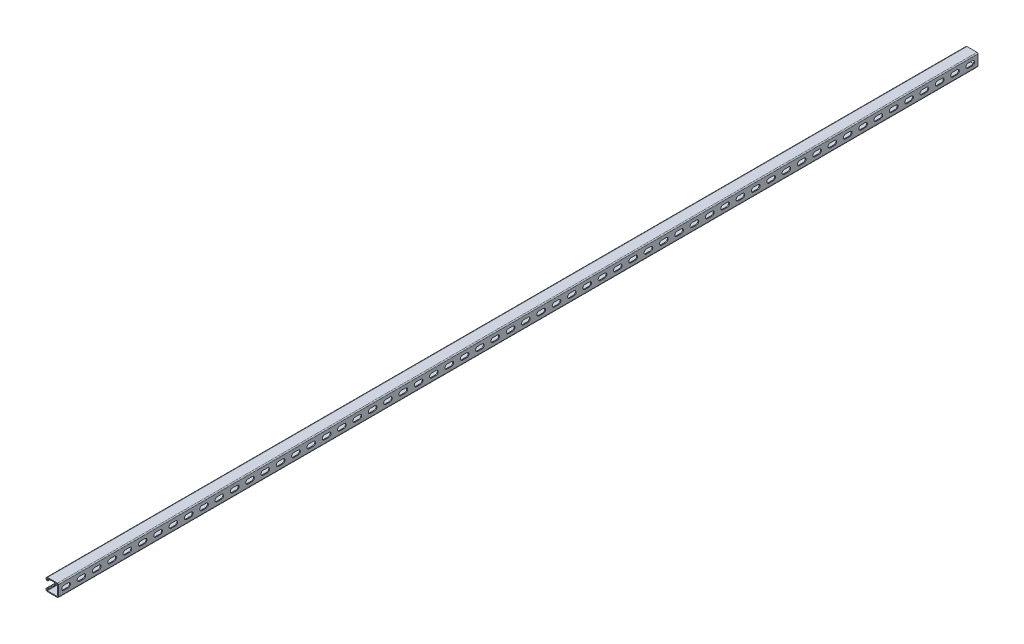
SolidWorks part; units mm, degrees
ref_plane "Front Plane" through (0, 0, 0) normal (0, 0, 1) x (1, 0, 0)
ref_plane "Top Plane" through (0, 0, 0) normal (0, 1, 0) x (1, 0, 0)
ref_plane "Right Plane" through (0, 0, 0) normal (1, 0, 0) x (0, 0, -1)
sketch "Sketch1" plane through (0, 0, 0) normal (0, 0, 1) x (1, 0, 0)
  line L0 (0, 0) -> (-41.275, 0) construction
  line L3 (-41.275, 20.6375) -> (0, 20.6375) construction
  line L4 (-41.275, 20.6375) -> (-41.275, -20.6375) construction
  line L5 (-41.275, -20.6375) -> (0, -20.6375) construction
  line L6 (0, 20.6375) -> (0, -20.6375) construction
  line L7 (-36.2267, 20.6375) -> (-3.4607, 20.6375)
  line L8 (0, 17.1767) -> (0, -17.1767)
  line L9 (-2.794, -17.1767) -> (-2.794, 17.1767)
  line L10 (-3.4608, 17.8435) -> (-36.2267, 17.8435)
  line L11 (-41.275, 15.5892) -> (-41.275, 14.5732)
  line L12 (-37.8142, 11.1125) -> (-35.5346, 11.1125)
  line L14 (-35.5346, 13.9065) -> (-37.8142, 13.9065)
  line L15 (-38.481, 14.5732) -> (-38.481, 15.5892)
  line L16 (-38.481, -14.5733) -> (-38.481, -15.5893)
  line L17 (-35.5346, -13.9065) -> (-37.8142, -13.9065)
  line L18 (-37.8142, -11.1125) -> (-35.5346, -11.1125)
  line L19 (-41.275, -15.5893) -> (-41.275, -14.5733)
  line L20 (-3.4607, -17.8435) -> (-36.2267, -17.8435)
  line L21 (-36.2267, -20.6375) -> (-3.4607, -20.6375)
  line L22 (-2.794, -20.6375) -> (-2.794, 20.6375) construction
  arc A1 (0, 17.1767) -> (-3.4607, 20.6375) centre (-3.4607, 17.1767) ccw
  arc A2 (-2.794, 17.1767) -> (-3.4608, 17.8435) centre (-3.4607, 17.1767) ccw
  arc A4 (-36.2267, 20.6375) -> (-41.275, 15.5892) centre (-36.2267, 15.5892) ccw
  arc A5 (-41.275, 14.5732) -> (-37.8142, 11.1125) centre (-37.8142, 14.5732) ccw
  arc A6 (-35.5346, 11.1125) -> (-35.5346, 13.9065) centre (-35.5346, 12.5095) ccw
  arc A7 (-37.8142, 13.9065) -> (-38.481, 14.5732) centre (-37.8142, 14.5732) cw
  arc A8 (-38.481, 15.5892) -> (-36.2267, 17.8435) centre (-36.2267, 15.5892) cw
  arc A9 (-38.481, -15.5893) -> (-36.2267, -17.8435) centre (-36.2267, -15.5893) ccw
  arc A10 (-37.8142, -13.9065) -> (-38.481, -14.5733) centre (-37.8142, -14.5733) ccw
  arc A11 (-35.5346, -11.1125) -> (-35.5346, -13.9065) centre (-35.5346, -12.5095) cw
  arc A12 (-41.275, -14.5733) -> (-37.8142, -11.1125) centre (-37.8142, -14.5733) cw
  arc A13 (-36.2267, -20.6375) -> (-41.275, -15.5893) centre (-36.2267, -15.5893) cw
  arc A14 (-2.794, -17.1767) -> (-3.4607, -17.8435) centre (-3.4607, -17.1767) cw
  arc A15 (0, -17.1767) -> (-3.4607, -20.6375) centre (-3.4607, -17.1767) cw
  point P24 (0, 20.6375)
  point P65 (-2.794, 0)
  dimension "D1" = 3.4608
  dimension "D2" = 5.0482
  dimension "D3" = 3.4608
  dimension "Ht." = 41.275
  dimension "Wd." = 41.275
  dimension "Thk." = 2.794
  dimension "D4" = 9.525
  dimension "D5" = 7.1374
extrude "Boss-Extrude1" add sketch "Sketch1" against normal blind 2540
sketch "Sketch4" plane through (0, 0, -2540) normal (0, 0, -1) x (-1, 0, 0)
  line L14 (36.2267, 20.6375) -> (3.4607, 20.6375)
  line L15 (0, 17.1767) -> (0, -17.1767)
  line L16 (3.4607, -20.6375) -> (36.2267, -20.6375)
  line L17 (41.275, -15.5893) -> (41.275, -14.5733)
  line L18 (37.8142, -11.1125) -> (35.5346, -11.1125)
  line L19 (35.5346, -13.9065) -> (37.8142, -13.9065)
  line L20 (38.481, -14.5733) -> (38.481, -15.5893)
  line L21 (36.2267, -17.8435) -> (3.4607, -17.8435)
  line L22 (2.794, -17.1767) -> (2.794, 17.1767)
  line L23 (3.4608, 17.8435) -> (36.2267, 17.8435)
  line L24 (38.481, 15.5892) -> (38.481, 14.5732)
  line L25 (37.8142, 13.9065) -> (35.5346, 13.9065)
  line L26 (35.5346, 11.1125) -> (37.8142, 11.1125)
  line L27 (41.275, 14.5732) -> (41.275, 15.5892)
  line L28 (36.2267, 20.6375) -> (3.4607, 20.6375)
  line L29 (0, 17.1767) -> (0, -17.1767)
  line L30 (3.4607, -20.6375) -> (36.2267, -20.6375)
  line L31 (41.275, -15.5893) -> (41.275, -14.5733)
  line L32 (37.8142, -11.1125) -> (35.5346, -11.1125)
  line L33 (35.5346, -13.9065) -> (37.8142, -13.9065)
  line L34 (38.481, -14.5733) -> (38.481, -15.5893)
  line L35 (36.2267, -17.8435) -> (3.4607, -17.8435)
  line L36 (2.794, -17.1767) -> (2.794, 17.1767)
  line L37 (3.4608, 17.8435) -> (36.2267, 17.8435)
  line L38 (38.481, 15.5892) -> (38.481, 14.5732)
  line L39 (37.8142, 13.9065) -> (35.5346, 13.9065)
  line L40 (35.5346, 11.1125) -> (37.8142, 11.1125)
  line L41 (41.275, 14.5732) -> (41.275, 15.5892)
  arc A14 (41.275, 15.5892) -> (36.2267, 20.6375) centre (36.2267, 15.5892) ccw
  arc A15 (3.4607, 20.6375) -> (0, 17.1767) centre (3.4607, 17.1767) ccw
  arc A16 (0, -17.1767) -> (3.4607, -20.6375) centre (3.4607, -17.1767) ccw
  arc A17 (36.2267, -20.6375) -> (41.275, -15.5893) centre (36.2267, -15.5893) ccw
  arc A18 (41.275, -14.5733) -> (37.8142, -11.1125) centre (37.8142, -14.5733) ccw
  arc A19 (35.5346, -11.1125) -> (35.5346, -13.9065) centre (35.5346, -12.5095) ccw
  arc A20 (38.481, -14.5733) -> (37.8142, -13.9065) centre (37.8142, -14.5733) ccw
  arc A21 (36.2267, -17.8435) -> (38.481, -15.5893) centre (36.2267, -15.5893) ccw
  arc A22 (2.794, -17.1767) -> (3.4607, -17.8435) centre (3.4607, -17.1767) ccw
  arc A23 (3.4608, 17.8435) -> (2.794, 17.1767) centre (3.4607, 17.1767) ccw
  arc A24 (38.481, 15.5892) -> (36.2267, 17.8435) centre (36.2267, 15.5892) ccw
  arc A25 (37.8142, 13.9065) -> (38.481, 14.5732) centre (37.8142, 14.5732) ccw
  arc A26 (35.5346, 13.9065) -> (35.5346, 11.1125) centre (35.5346, 12.5095) ccw
  arc A27 (37.8142, 11.1125) -> (41.275, 14.5732) centre (37.8142, 14.5732) ccw
  arc A28 (41.275, 15.5892) -> (36.2267, 20.6375) centre (36.2267, 15.5892) ccw
  arc A29 (3.4607, 20.6375) -> (0, 17.1767) centre (3.4607, 17.1767) ccw
  arc A30 (0, -17.1767) -> (3.4607, -20.6375) centre (3.4607, -17.1767) ccw
  arc A31 (36.2267, -20.6375) -> (41.275, -15.5893) centre (36.2267, -15.5893) ccw
  arc A32 (41.275, -14.5733) -> (37.8142, -11.1125) centre (37.8142, -14.5733) ccw
  arc A33 (35.5346, -11.1125) -> (35.5346, -13.9065) centre (35.5346, -12.5095) ccw
  arc A34 (38.481, -14.5733) -> (37.8142, -13.9065) centre (37.8142, -14.5733) ccw
  arc A35 (36.2267, -17.8435) -> (38.481, -15.5893) centre (36.2267, -15.5893) ccw
  arc A36 (2.794, -17.1767) -> (3.4607, -17.8435) centre (3.4607, -17.1767) ccw
  arc A37 (3.4608, 17.8435) -> (2.794, 17.1767) centre (3.4607, 17.1767) ccw
  arc A38 (38.481, 15.5892) -> (36.2267, 17.8435) centre (36.2267, 15.5892) ccw
  arc A39 (37.8142, 13.9065) -> (38.481, 14.5732) centre (37.8142, 14.5732) ccw
  arc A40 (35.5346, 13.9065) -> (35.5346, 11.1125) centre (35.5346, 12.5095) ccw
  arc A41 (37.8142, 11.1125) -> (41.275, 14.5732) centre (37.8142, 14.5732) ccw
  dimension "D1" = 0
extrude "Boss-Extrude2" add sketch "Sketch4" along normal blind 508
sketch "Sketch3" plane through (0, 0, 0) normal (1, 0, 0) x (0, 0, -1)
  line L0 (0, 0) -> (2540, 0) construction
  point P2 (101.6, 0)
  point P3 (2438.4, 0)
  dimension "D1" = 101.6
  dimension "D2" = 101.6
  dimension "D3" = 2540
sketch "Sketch2" plane through (0, 0, 0) normal (1, 0, 0) x (0, 0, -1)
  line L0 (18.2562, 0) -> (32.5437, 0) construction
  line L1 (18.2562, 7.1438) -> (32.5437, 7.1438)
  line L2 (18.2562, -7.1438) -> (32.5437, -7.1438)
  line L3 (18.2562, 0) -> (0, 0) construction
  line L4 (25.4, 0) -> (76.2, 0) construction
  line L5 (0, -17.1767) -> (0, 17.1767) construction
  arc A0 (18.2562, 7.1438) -> (18.2562, -7.1438) centre (18.2562, 0) ccw
  arc A1 (32.5437, -7.1438) -> (32.5437, 7.1438) centre (32.5437, 0) ccw
  point P3 (25.4, 0)
  dimension "Slot Lg." = 28.575
  dimension "D2" = 25.4
  dimension "Slot Wd." = 14.2875
  dimension "Slot Ctr." = 50.8
  dimension "Hole to End" = 11.1125
extrude "Cut-Extrude1" cut sketch "Sketch2" against normal up to vertex (2.794 mm away) up to point (-2.794, 0, 0)
pattern_linear "LPattern1" count 60 spacing 50.8 along (0, 0, -1) of "Cut-Extrude1"
equation "\"D3@Sketch3\" = \"Lg.@Boss-Extrude1\""
